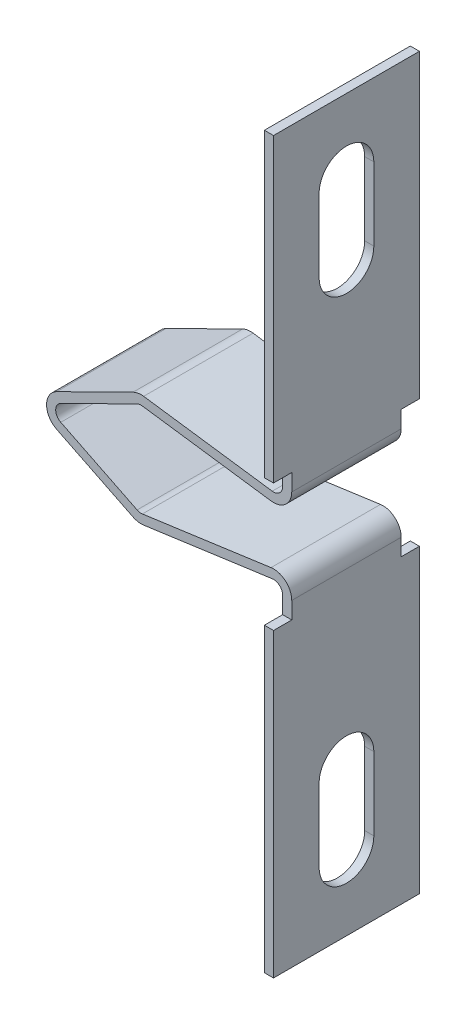
SolidWorks part; units mm, degrees
ref_plane "前视基准面" through (0, 0, 0) normal (0, 0, 1) x (1, 0, 0)
ref_plane "上视基准面" through (0, 0, 0) normal (0, 1, 0) x (1, 0, 0)
ref_plane "右视基准面" through (0, 0, 0) normal (1, 0, 0) x (0, 0, -1)
sketch "草图1" plane through (0, 0, 0) normal (0, 0, 1) x (1, 0, 0)
  line L0 (0, 0) -> (6.276, 3.1)
  line L1 (6.276, 3.1) -> (14.2, 2)
  line L2 (14.2, 2) -> (14.2, 20)
  line L3 (0, 0) -> (72.3734, 0) construction
  line L4 (0, 0) -> (6.276, -3.1)
  line L5 (6.276, -3.1) -> (14.2, -2)
  line L6 (14.2, -2) -> (14.2, -20)
  line L7 (14.7, -1.4258) -> (14.7, -20)
  line L8 (6.3595, -2.5836) -> (14.7, -1.4258)
  line L9 (1.129, 0) -> (6.3595, -2.5836)
  line L10 (1.129, 0) -> (6.3595, 2.5836)
  line L11 (6.3595, 2.5836) -> (14.7, 1.4258)
  line L12 (14.7, 1.4258) -> (14.7, 20)
  line L13 (14.2, 20) -> (14.7, 20)
  line L14 (14.2, -20) -> (14.7, -20)
  dimension "D1" = 18
  dimension "D2" = 14.2
  dimension "D3" = 6.2
  dimension "D4" = 40
  dimension "D5" = 8
  dimension "D6" = 0.5
extrude "凸台-拉伸1" add sketch "草图1" along normal mid plane 8
fillet "圆角1" radius 0.5 5 edges at (14.2, -2, 0) (14.2, 2, 0) (6.3595, -2.5836, 0) (1.129, 0, 0) (6.3595, 2.5836, 0)
fillet "圆角2" radius 1 5 edges at (14.7, 1.4258, 0) (14.7, -1.4258, 0) (6.276, 3.1, 0) (6.276, -3.1, 0) (0, 0, 0)
sketch "草图2" plane through (14.2, 0, 0) normal (-1, 0, 0) x (0, 0, 1)
  line L0 (0, 16) -> (0, 12) construction
  line L1 (1.5, 16) -> (1.5, 12)
  line L2 (-1.5, 16) -> (-1.5, 12)
  line L3 (0, -12) -> (0, -16) construction
  line L4 (1.5, -12) -> (1.5, -16)
  line L5 (-1.5, -12) -> (-1.5, -16)
  line L6 (4, 20) -> (-4, 20) construction
  line L7 (4, -20) -> (-4, -20) construction
  arc A0 (1.5, 16) -> (-1.5, 16) centre (0, 16) ccw
  arc A1 (-1.5, 12) -> (1.5, 12) centre (0, 12) ccw
  arc A2 (1.5, -12) -> (-1.5, -12) centre (0, -12) ccw
  arc A3 (-1.5, -16) -> (1.5, -16) centre (0, -16) ccw
  point P3 (0, 14)
  point P8 (0, -14)
  point P17 (0, 20)
  dimension "D4" = 4
  dimension "D1" = 3
  dimension "D2" = 4
  dimension "D3" = 4
extrude "切除-拉伸1" cut sketch "草图2" against normal up to surface (0.5 mm away) up to face at (14.7, 11.2871, 0)
sketch "草图3" plane through (14.2, 0, 0) normal (-1, 0, 0) x (0, 0, 1)
  line L0 (0, 0) -> (0, 7.2251) construction
  line L1 (3, 3.5) -> (6.4442, 3.5)
  line L2 (3, 3.5) -> (3, -3.5)
  line L3 (3, -3.5) -> (6.4442, -3.5)
  line L4 (6.4442, 3.5) -> (6.4442, -3.5)
  line L5 (-5.5966, 3.5) -> (-3, 3.5)
  line L6 (-5.5966, 3.5) -> (-5.5966, -3.5)
  line L7 (-5.5966, -3.5) -> (-3, -3.5)
  line L8 (-3, 3.5) -> (-3, -3.5)
  line L9 (4, 20) -> (4, 2.5742) construction
  line L10 (0, 0) -> (10.9753, 0) construction
  dimension "D1" = 1
  dimension "D2" = 7
extrude "切除-拉伸2" cut sketch "草图3" against normal mid plane 34
